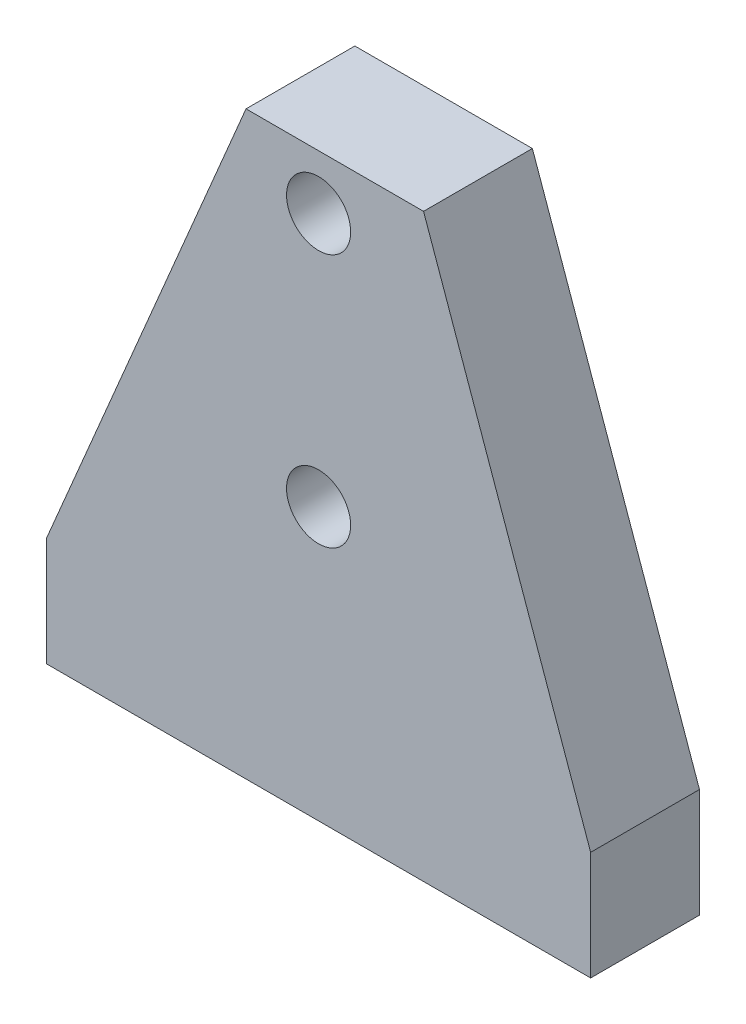
SolidWorks part; units mm, degrees
ref_plane "Front Plane" through (0, 0, 0) normal (0, 0, 1) x (1, 0, 0)
ref_plane "Top Plane" through (0, 0, 0) normal (0, 1, 0) x (1, 0, 0)
ref_plane "Right Plane" through (0, 0, 0) normal (1, 0, 0) x (0, 0, -1)
sketch "Sketch1" plane through (0, 0, 0) normal (0, 0, 1) x (1, 0, 0)
  line L0 (23.8125, -15.875) -> (9.1865, 25.4)
  line L1 (-23.8125, 25.4) -> (23.8125, 25.4)
  line L2 (-23.8125, 25.4) -> (-23.8125, -25.4)
  line L3 (-23.8125, -25.4) -> (23.8125, -25.4)
  line L4 (23.8125, 25.4) -> (23.8125, -25.4)
  line L7 (-23.8125, -15.875) -> (-6.35, 25.4)
  point P0 (0, 0)
  point P11 (0, 25.4)
  point P12 (9.1865, 25.4)
  dimension "D1" = 47.625
  dimension "D2" = 50.8
  dimension "D3" = 9.525
extrude "Boss-Extrude1" add sketch "Sketch1" along normal blind 9.525 contours L7 L2 L3 L4 L0 L1
hole_wizard "#10 Clearance Hole1" positions "Sketch3" profile "Sketch4" hole size "#10" standard "ANSI Inch" end condition through all
sketch "Sketch3" plane through (0, 0, 9.525) normal (0, 0, 1) x (1, 0, 0)
  line L0 (0, 20.6375) -> (0, -1.5875) construction
  line L4 (-23.8125, -15.875) -> (-23.8125, -25.4) construction
  line L5 (23.8125, -15.875) -> (23.8125, -25.4) construction
  circle A0 centre (0, 20.6375) radius 2.0193 construction
  circle A1 centre (0, -1.5875) radius 2.0193 construction
  point P0 (0, 20.6375)
  point P2 (0, -1.5875)
sketch "Sketch4" plane through (0, 20.6375, 9.525) normal (1, 0, 0) x (0, -1, 0)
  line L0 (0, 0) -> (0, 9.525)
  line L1 (0, 9.525) -> (2.8067, 9.525)
  line L2 (2.8067, 9.525) -> (2.8067, 0)
  line L5 (2.8067, 0) -> (0, 0)
  line L11 (0, -6.35) -> (0, 107.95) construction
  dimension "Thru Hole Dia." = 5.6134
  dimension "Thru Hole Depth" = 9.525
hole_wizard "M6x1.0 Tapped Hole1" positions "Sketch6" profile "Sketch5" tap size "M6x1.0" standard "ANSI Metric"
sketch "Sketch6" plane through (0, -25.4, 0) normal (0, -1, 0) x (-1, 0, 0)
  line L0 (13.9954, -4.7625) -> (-13.9954, -4.7625) construction
  line L2 (0, -4.7625) -> (0, 0) construction
  line L6 (23.8125, -9.525) -> (-23.8125, -9.525) construction
  line L7 (23.8125, 0) -> (-23.8125, 0) construction
  point P0 (13.9954, -4.7625)
  point P2 (-13.9954, -4.7625)
  dimension "D1" = 27.9908
sketch "Sketch5" plane through (-13.9954, -25.4, 4.7625) normal (1, 0, 0) x (0, 0, -1)
  line L0 (0, 0) -> (0, 13.0048)
  line L1 (0, 13.0048) -> (2.5, 13.0048)
  line L2 (2.5, 13.0048) -> (2.5, 0)
  line L5 (2.5, 0) -> (0, 0)
  line L10 (0, 13.0048) -> (-2.5, 13.0048) construction
  line L11 (0, -6.35) -> (0, 107.95) construction
  dimension "Tap Drill Dia." = 5
  dimension "Tap Drill Depth" = 13.0048
  dimension "Drill Angle" = 180
cosmetic thread "Hole Thread3" parameters "D1"=10.0076, "D2"=6
cosmetic thread "Hole Thread4" parameters "D1"=10.0076, "D2"=6
